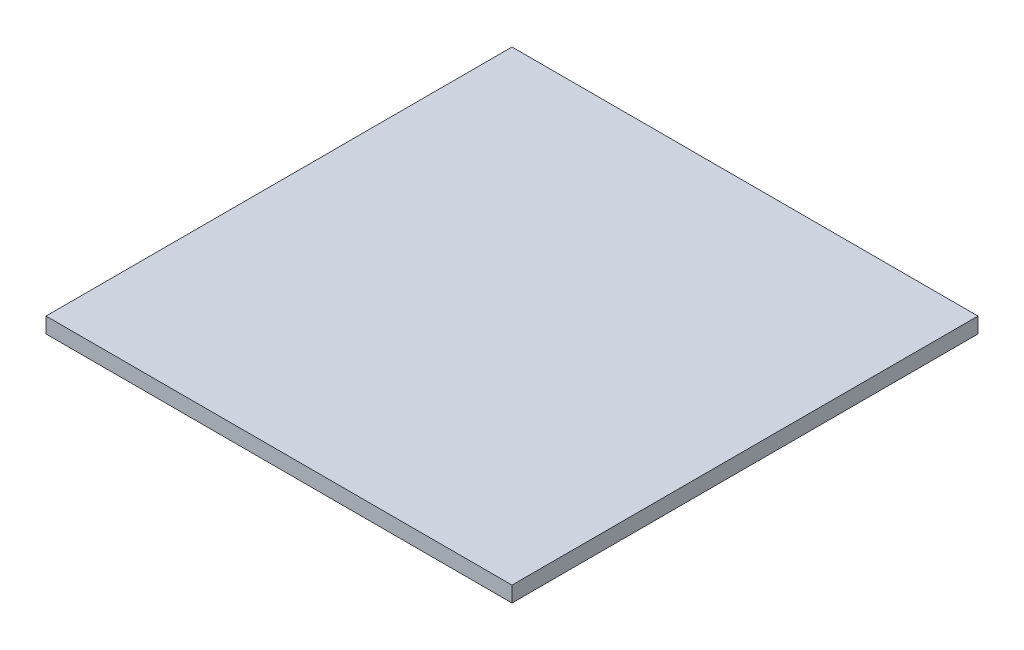
SolidWorks part; units mm, degrees
ref_plane "Front Plane" through (0, 0, 0) normal (0, 0, 1) x (1, 0, 0)
ref_plane "Top Plane" through (0, 0, 0) normal (0, 1, 0) x (1, 0, 0)
ref_plane "Right Plane" through (0, 0, 0) normal (1, 0, 0) x (0, 0, -1)
sketch "Sketch2" plane through (0, 0, 0) normal (0, 1, 0) x (1, 0, 0)
  line L1 (0, 0) -> (300, 0)
  line L2 (0, 0) -> (0, 300)
  line L3 (0, 300) -> (300, 300)
  line L4 (300, 0) -> (300, 300)
  line L5 (0, 0) -> (300, 300) construction
  line L6 (0, 300) -> (300, 0) construction
  point P4 (150, 150)
  dimension "D1" = 300
extrude "Boss-Extrude1" add sketch "Sketch2" along normal blind 10
